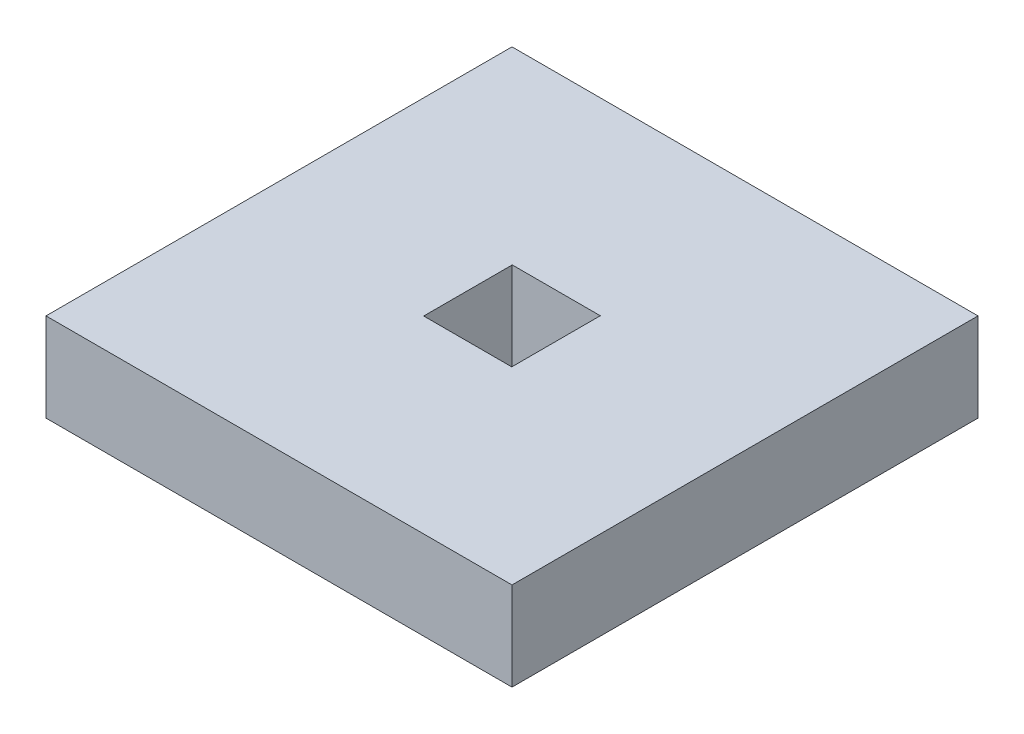
SolidWorks part; units mm, degrees
ref_plane "Front Plane" through (0, 0, 0) normal (0, 0, 1) x (1, 0, 0)
ref_plane "Top Plane" through (0, 0, 0) normal (0, 1, 0) x (1, 0, 0)
ref_plane "Right Plane" through (0, 0, 0) normal (1, 0, 0) x (0, 0, -1)
sketch "Sketch1" plane through (0, 0, 0) normal (0, 1, 0) x (1, 0, 0)
  line L1 (0, 0) -> (25.4, 0)
  line L2 (0, 0) -> (0, 25.4)
  line L3 (0, 25.4) -> (25.4, 25.4)
  line L4 (25.4, 0) -> (25.4, 25.4)
  line L5 (0, 0) -> (25.4, 25.4) construction
  line L6 (0, 25.4) -> (25.4, 0) construction
  point P4 (12.7, 12.7)
  dimension "D1" = 25.4
  dimension "D2" = 25.4
extrude "Boss-Extrude1" add sketch "Sketch1" along normal blind 4.826
ref_plane "Plane1" through (0, 0, -12.7) normal (0, 0, -1) x (-1, 0, 0)
ref_plane "Plane2" through (12.7, 0, 0) normal (-1, 0, 0) x (0, 0, 1)
sketch "Sketch2" plane through (0, 4.826, 0) normal (0, 1, 0) x (1, 0, 0)
  line L8 (15.1, 15.113) -> (10.3, 15.113)
  line L9 (15.1, 10.287) -> (15.1, 15.113)
  line L10 (10.3, 10.287) -> (15.1, 10.287)
  line L11 (10.3, 15.113) -> (10.3, 10.287)
ref_point "Point1"
extrude "Cut-Extrude1" cut sketch "Sketch2" against normal through all
equation "\"MDF\"= 4.8mm"
equation "\"Foamcore\"= 4.6mm"
equation "\"GMaterial\"= \"MDF\""
equation "\"PCB\" = 1.6mm"
equation "\"BaseWidth\" = 10in"
equation "\"SkidLength\" = 1in"
equation "\"SkidClearance\" = 0.4in"
equation "\"MotorMountWidth\" = \"GMaterial\""
equation "\"MotorMountHeight\" = 2.25in"
equation "\"UnoStackWidth\" = 77.4mm"
equation "\"UnoStackLength\" = 79.8mm"
equation "\"UnoStackHeight\" = 34.2mm"
equation "\"TallHexRiserHeight\" = 22.2mm"
equation "\"PingPongBallSize\" = 40mm"
equation "\"BarrelLength\" = 9in"
equation "\"BarrelSize\" = \"PingPongBallSize\""
equation "\"PlatformLength\" = 4in"
equation "\"PlatformWidth\" = 6in"
equation "\"WheelDiameter\"=2.99213"
equation "\"ServoMountHeight\"=2.49223"
equation "\"ServoGearHeight\" = 0.95330261in"
equation "\"ServoMountLength\"= 1.53774"
equation "\"PivotHoleRadius\"= 0.616358"
equation "\"PlatformMountHeight\" = 3.19"
equation "\"TensionOffSet\"= .3mm"
equation "\"MotorMountWedge\"=0.333333"
equation "\"LaserCutterOffset\"= .3mm"
equation "\"BumperWidth\"=11"
equation "\"PitcherWheelCompression\" = 2.5mm"
equation "\"PitchingWheelWidth\" = 26.2mm"
equation "\"PitchingWheelDiameter\" = 65.5mm"
equation "\"PitchingWheelMountOffset\" = 8.4mm"
equation "\"PitchingWheelInnerDiameter\" = 45.5mm"
equation "\"PitchingWheelBoltShoulder\" = 4.5mm"
equation "\"BrassCouplingLength\" = 18mm"
equation "\"PitchingMotorHeight\" = 57.0mm"
equation "\"PitchingMotorShaftTopHeight\" = \"PitchingMotorHeight\" - 44.1mm"
equation "\"PitchingMotorBodyHeight\" = 38mm"
equation "\"PitchingMotorTopShoulderHeight\" = 40.6mm - \"PitchingMotorBodyHeight\" "
equation "\"PitchingMotorBottomShoulderHeight\" = 40.2mm - \"PitchingMotorBodyHeight\""
equation "\"PitchingMotorBottomShaftHeight\" = \"PitchingMotorHeight\" - \"PitchingMotorShaftTopHeight\" - \"PitchingMotorTopShoulderHeight\" - \"PitchingMotorBodyHeight\" - \"PitchingMotorBottomShoulderHeight\""
equation "\"PitchingMotorShaftDiameter\" = 2.2mm"
equation "\"PitchingMotorBodyDiameter\" = 27.4mm"
equation "\"PitchingMotorTopShoulderDiameter\" = 9.8mm"
equation "\"PitchingMotorBottomShoulderDiameter\" = 9.8mm"
equation "\"BrassCouplingHexSize\" = 12mm"
equation "\"BrassCouplingBoreSize\" = 3.17mm"
equation "\"PitchingMotorMountingHoleDistance\" = 16mm"
equation "\"Acrylic\" = 4.4mm"
equation "\"PitchingMotorDistance\" = \"PitchingWheelDiameter\" + \"PingPongBallSize\" - \"PitcherWheelCompression\"*2"
equation "\"PitchingMotorPlatformOffset\"=1"
equation "\"ServoPlatformOffset\"=1.64173"
equation "\"BallBearingDiameter\" = 22mm"
equation "\"BallBearingWidth\" = 9mm"
equation "\"BallBearingHexShoulder\" = 9mm - 5.9mm"
equation "\"BallBearingHexSize\" = .36in"
equation "\"PlatformMountFootLength\"=0.857143"
equation "\"WheelWidth\"= 26mm"
equation "\"ServoMountReductionBackHeight\"=2.25"
equation "\"PlatformBottomWidthThird\" =  0.857143in"
equation "\"PlatformMountBackReductionHeight\"= 2.5in"
equation "\"PlatformMountBackReductionWidth\"= 3/7in"
equation "\"PlatformMountFrontReductionWidth\" =  1.46226in"
equation "\"PlatformMountFrontReductionHeight\" = 2.5in"
